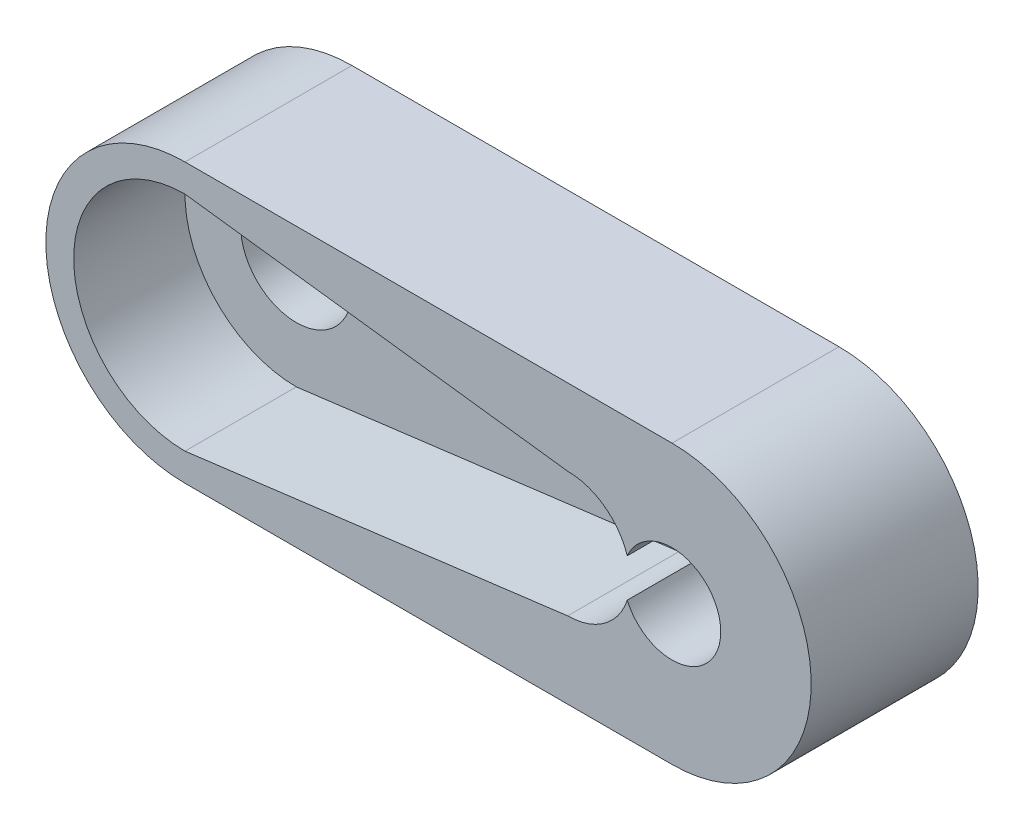
SolidWorks part; units mm, degrees
ref_plane "Plan de face" through (0, 0, 0) normal (0, 0, 1) x (1, 0, 0)
ref_plane "Plan de dessus" through (0, 0, 0) normal (0, 1, 0) x (1, 0, 0)
ref_plane "Plan de droite" through (0, 0, 0) normal (1, 0, 0) x (0, 0, -1)
sketch "Esquisse1" plane through (0, 0, 0) normal (0, 0, 1) x (1, 0, 0)
  line L1 (0, 0) -> (17.5, 0)
  line L2 (0, 0) -> (0, 10) construction
  line L3 (0, 10) -> (17.5, 10)
  line L4 (17.5, 0) -> (17.5, 10) construction
  arc A0 (0, 10) -> (0, 0) centre (0, 5) ccw
  arc A1 (17.5, 10) -> (17.5, 0) centre (17.5, 5) cw
  circle A2 centre (0, 5) radius 2
  circle A3 centre (17.5, 5) radius 1.75
  dimension "D3" = 4
  dimension "D4" = 3.5
  dimension "D1" = 10
  dimension "D2" = 17.5
extrude "Boss.-Extru.1" add sketch "Esquisse1" along normal blind 6
sketch "Esquisse2" plane through (0, 0, 6) normal (0, 0, 1) x (1, 0, 0)
  line L0 (0, 5) -> (13.75, 5) construction
  line L1 (0, 9) -> (13.75, 7.25)
  line L2 (-4, 5) -> (16, 5) construction
  line L3 (0, 1) -> (13.75, 2.75)
  arc A0 (1.002, 8.8725) -> (1.002, 1.1275) centre (0, 5) ccw
  arc A1 (13.75, 2.75) -> (13.75, 7.25) centre (13.75, 5) ccw
  circle M4 centre (0, 5) radius 2
  circle M9 centre (17.5, 5) radius 1.75
  dimension "D1" = 8
  dimension "D2" = 4.5
  dimension "D3" = 20
extrude "Enlèv. mat.-Extru.1" cut sketch "Esquisse2" against normal blind 4 contours A1 L1 A0 L3 M9 M4
chamfer "Chanfrein2" distance 1.25 angle 45 1 edges at (19.25, 5, 0)
